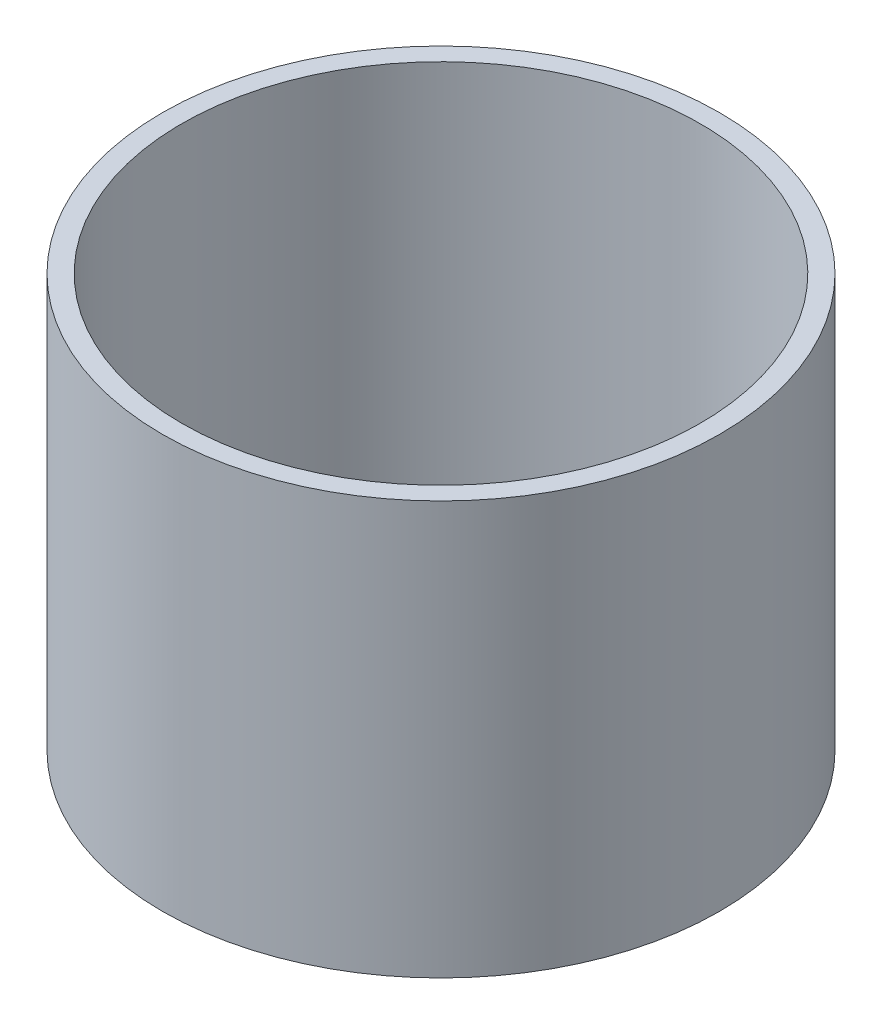
SolidWorks part; units mm, degrees
ref_plane "Front Plane" through (0, 0, 0) normal (0, 0, 1) x (1, 0, 0)
ref_plane "Top Plane" through (0, 0, 0) normal (0, 1, 0) x (1, 0, 0)
ref_plane "Right Plane" through (0, 0, 0) normal (1, 0, 0) x (0, 0, -1)
sketch "Sketch1" plane through (0, 0, 0) normal (0, 1, 0) x (1, 0, 0)
  circle A1 centre (0, 0) radius 68.58
  circle A2 centre (0, 0) radius 73.66
  dimension "D1" = 137.16
  dimension "D3" = 5.08
extrude "Boss-Extrude1" add sketch "Sketch1" along normal blind 104.14
sketch "Sketch2" plane through (0, 0, 0) normal (0, -1, 0) x (1, 0, 0)
  circle A0 centre (0, 0) radius 73.66
  circle A1 centre (0, 48.26) radius 3.3782
  circle A2 centre (48.26, 0) radius 3.3782
  circle A3 centre (0, -48.26) radius 3.3782
  circle A4 centre (-48.26, 0) radius 3.3782
  point P14 (0, 0)
  dimension "D1" = 6.7564
  dimension "D2" = 48.26
  dimension "D3" = 4
extrude "Boss-Extrude2" add sketch "Sketch2" along normal blind 5.08
